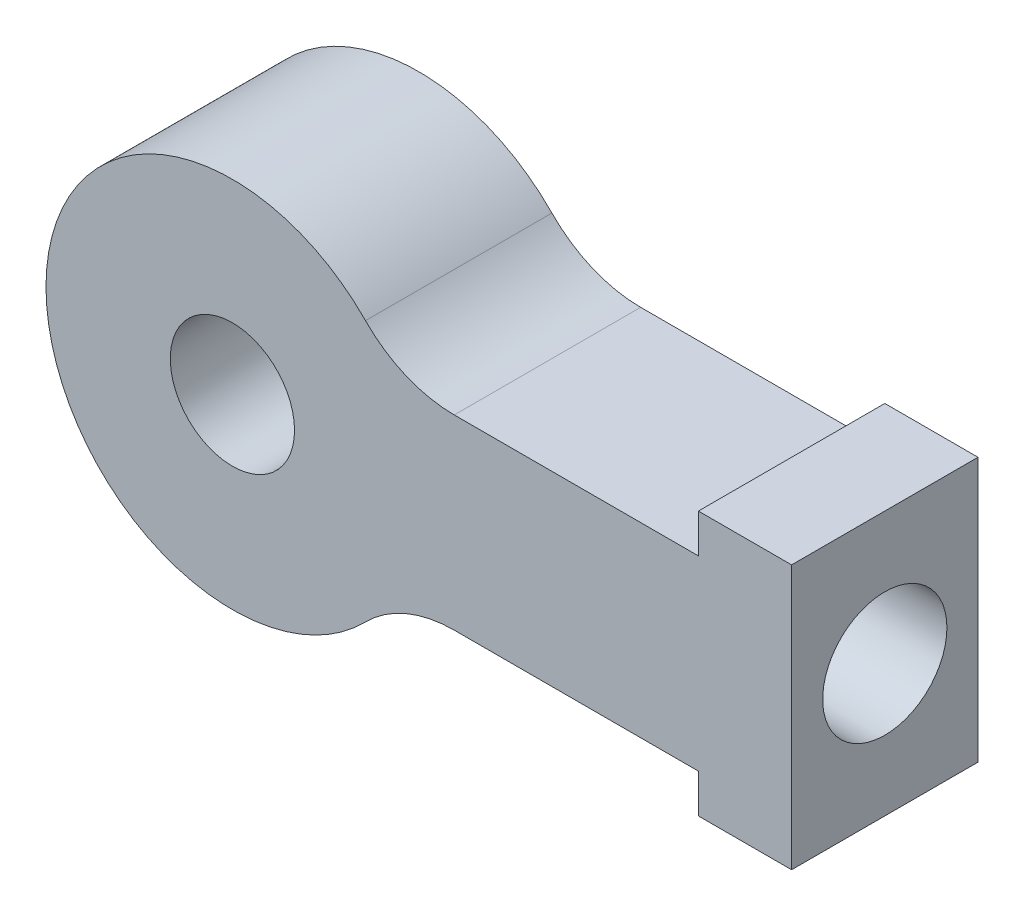
SolidWorks part; units mm, degrees
ref_plane "前视基准面" through (0, 0, 0) normal (0, 0, 1) x (1, 0, 0)
ref_plane "上视基准面" through (0, 0, 0) normal (0, 1, 0) x (1, 0, 0)
ref_plane "右视基准面" through (0, 0, 0) normal (1, 0, 0) x (0, 0, -1)
sketch "草图2" plane through (0, 0, 0) normal (0, 0, 1) x (1, 0, 0)
  line L0 (14.2829, 6) -> (30, 6)
  line L1 (30, -8.5) -> (30, -6)
  line L2 (30, 8.5) -> (36, 8.5)
  line L3 (36, 8.5) -> (36, 0)
  line L4 (14.2829, -6) -> (30, -6)
  line L5 (30, -8.5) -> (36, -8.5)
  line L6 (36, -8.5) -> (36, 0)
  line L7 (30, 6) -> (30, 8.5)
  arc A0 (8.5697, 8.4) -> (8.5697, -8.4) centre (0, 0) ccw
  circle A1 centre (0, 0) radius 4
  arc A2 (8.5697, 8.4) -> (14.2829, 6) centre (14.2829, 14) ccw
  arc A3 (14.2829, -6) -> (8.5697, -8.4) centre (14.2829, -14) ccw
extrude "凸台-拉伸1" add sketch "草图2" along normal blind 12
sketch "草图3" plane through (36, 0, 0) normal (1, 0, 0) x (0, 0, -1)
  circle A0 centre (-6, 0) radius 4
  dimension "D1" = 8
extrude "切除-拉伸1" cut sketch "草图3" against normal blind 20
